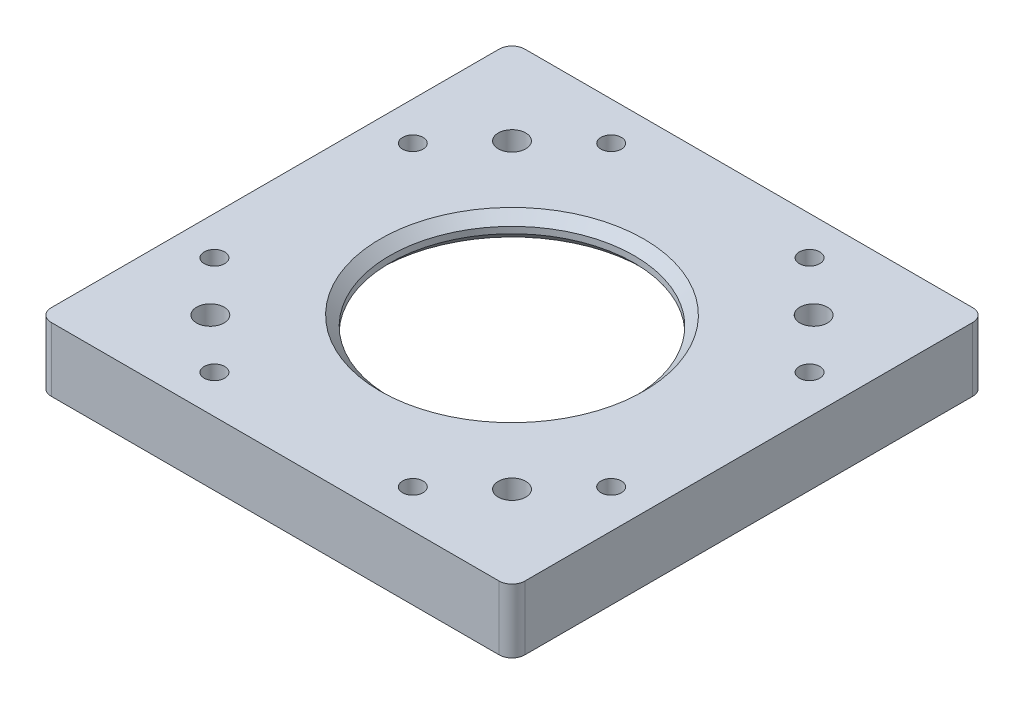
SolidWorks part; units mm, degrees
ref_plane "Front Plane" through (0, 0, 0) normal (0, 0, 1) x (1, 0, 0)
ref_plane "Top Plane" through (0, 0, 0) normal (0, 1, 0) x (1, 0, 0)
ref_plane "Right Plane" through (0, 0, 0) normal (1, 0, 0) x (0, 0, -1)
sketch "Sketch1" plane through (0, 0, 0) normal (0, 1, 0) x (1, 0, 0)
  line L0 (30, 0) -> (0, 0) construction
  line L1 (-37, -37) -> (37, -37)
  line L2 (-37, -37) -> (-37, 37)
  line L3 (-37, 37) -> (37, 37)
  line L4 (37, -37) -> (37, 37)
  line L5 (-37, -37) -> (37, 37) construction
  line L6 (-37, 37) -> (37, -37) construction
  line L7 (-23.57, -23.57) -> (23.57, -23.57) construction
  line L8 (-23.57, -23.57) -> (-23.57, 23.57) construction
  line L9 (-23.57, 23.57) -> (23.57, 23.57) construction
  line L10 (23.57, -23.57) -> (23.57, 23.57) construction
  line L11 (-23.57, -23.57) -> (23.57, 23.57) construction
  line L12 (-23.57, 23.57) -> (23.57, -23.57) construction
  line L13 (0, 37) -> (0, 31) construction
  line L14 (0, 31) -> (15.5, 31) construction
  line L15 (37, 0) -> (31, 0) construction
  line L16 (31, 0) -> (31, -15.5) construction
  line L17 (0, -37) -> (0, -31) construction
  line L18 (0, -31) -> (-15.5, -31) construction
  line L19 (-37, 0) -> (-31, 0) construction
  line L20 (-31, 0) -> (-31, 15.5) construction
  circle A1 centre (23.57, 23.57) radius 2.15
  circle A2 centre (-23.57, 23.57) radius 2.15
  circle A3 centre (-23.57, -23.57) radius 2.15
  circle A4 centre (23.57, -23.57) radius 2.15
  circle A5 centre (0, 0) radius 19.1
  circle A6 centre (15.5, 31) radius 1.6
  circle A7 centre (-15.5, 31) radius 1.6
  circle A8 centre (31, -15.5) radius 1.6
  circle A9 centre (31, 15.5) radius 1.6
  circle A10 centre (-15.5, -31) radius 1.6
  circle A11 centre (15.5, -31) radius 1.6
  circle A12 centre (-31, 15.5) radius 1.6
  circle A13 centre (-31, -15.5) radius 1.6
  point P0 (0, 0)
  point P47 (0, 0)
  dimension "D3" = 47.14
  dimension "D4" = 38.2
  dimension "D7" = 4
  dimension "D1" = 74
  dimension "D2" = 74
  dimension "D5" = 6
  dimension "D6" = 15.5
extrude "Boss-Extrude1" add sketch "Sketch1" along normal blind 10
sketch "Sketch2" plane through (0, 0, 0) normal (0, -1, 0) x (1, 0, 0)
  line L1 (-28.6, -28.6) -> (28.6, -28.6)
  line L2 (-28.6, -28.6) -> (-28.6, 28.6)
  line L3 (-28.6, 28.6) -> (28.6, 28.6)
  line L4 (28.6, -28.6) -> (28.6, 28.6)
  line L5 (-28.6, -28.6) -> (28.6, 28.6) construction
  line L6 (-28.6, 28.6) -> (28.6, -28.6) construction
  point P0 (0, 0)
  dimension "D1" = 57.2
  dimension "D2" = 57.2
extrude "Cut-Extrude1" cut sketch "Sketch2" against normal blind 6
fillet "Fillet1" radius 3 4 edges at (28.6, 3, 28.6) (28.6, 3, -28.6) (-28.6, 3, -28.6) (-28.6, 3, 28.6)
chamfer "Chamfer1" distance 1.5 angle 45 2 edges at (0, 10, 19.1) (0, 6, 19.1)
fillet "Fillet2" radius 2 4 edges at (-37, 5, -37) (37, 5, -37) (37, 5, 37) (-37, 5, 37)
